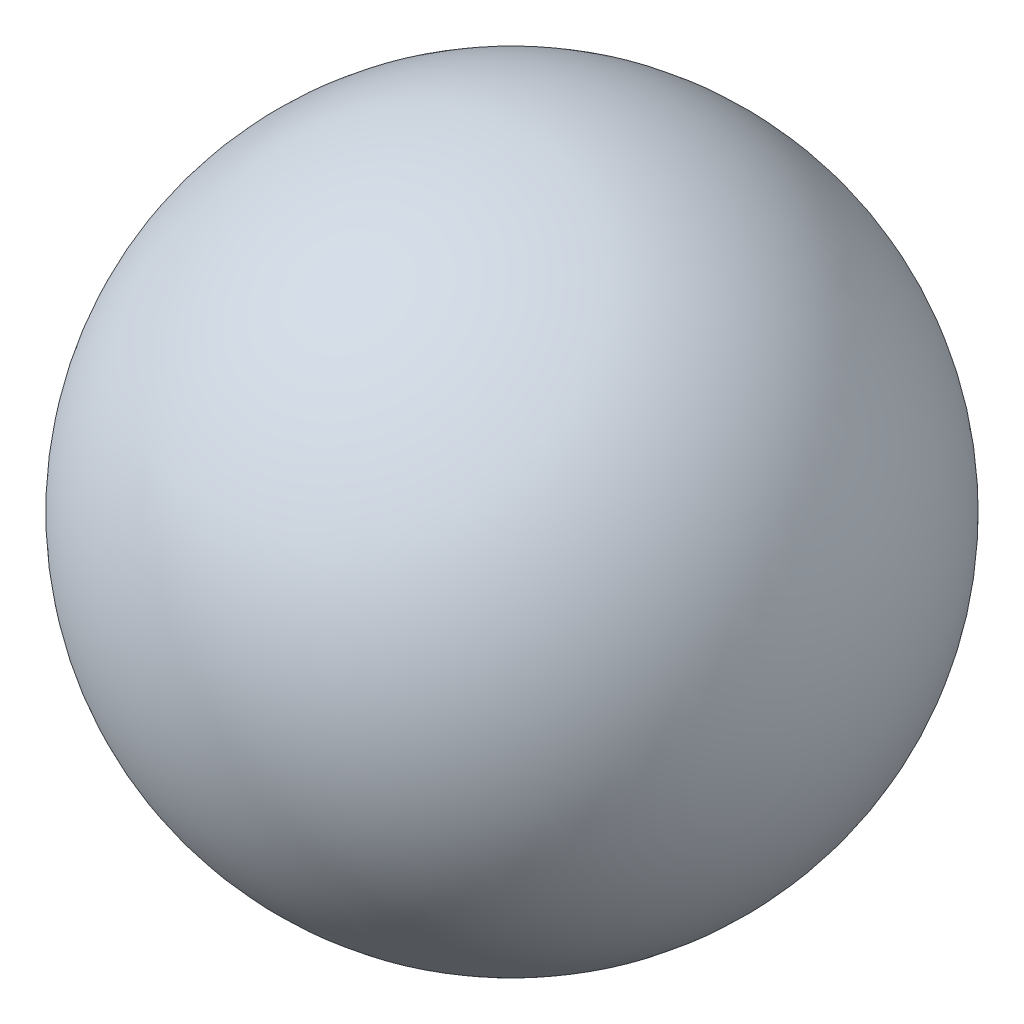
SolidWorks part; units mm, degrees
ref_plane "Front Plane" through (0, 0, 0) normal (0, 0, 1) x (1, 0, 0)
ref_plane "Top Plane" through (0, 0, 0) normal (0, 1, 0) x (1, 0, 0)
ref_plane "Right Plane" through (0, 0, 0) normal (1, 0, 0) x (0, 0, -1)
sketch "Sketch1" plane through (0, 0, 0) normal (1, 0, 0) x (0, 0, -1)
  line L0 (0, 1.75) -> (0, -1.75)
  arc A0 (0, 1.75) -> (0, -1.75) centre (0, 0) ccw
  dimension "D1" = 3.5
revolve "Revolve1" add sketch "Sketch1" angle 360 about L0
